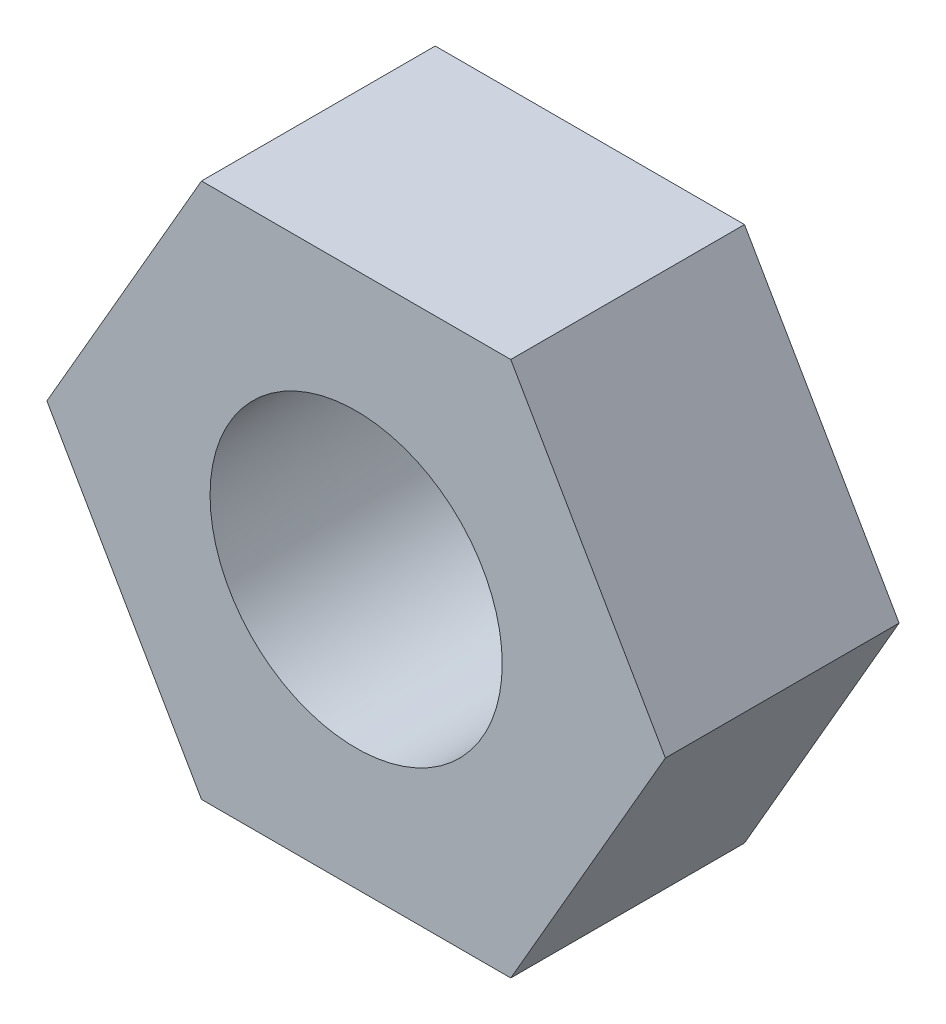
SolidWorks part; units mm, degrees
material "AISI 4340 Steel, normalized"
ref_plane "Front Plane" through (0, 0, 0) normal (0, 0, 1) x (1, 0, 0)
ref_plane "Top Plane" through (0, 0, 0) normal (0, 1, 0) x (1, 0, 0)
ref_plane "Right Plane" through (0, 0, 0) normal (1, 0, 0) x (0, 0, -1)
sketch "Sketch1" plane through (0, 0, 0) normal (0, 0, 1) x (1, 0, 0)
  line L0 (3.1754, 0) -> (1.5877, 2.75)
  line L1 (1.5877, 2.75) -> (-1.5877, 2.75)
  line L2 (-1.5877, 2.75) -> (-3.1754, 0)
  line L3 (-3.1754, 0) -> (-1.5877, -2.75)
  line L4 (-1.5877, -2.75) -> (1.5877, -2.75)
  line L5 (1.5877, -2.75) -> (3.1754, 0)
  circle A0 centre (0, 0) radius 1.5
extrude "Nut_Thread_Major_Envelope" add sketch "Sketch1" along normal blind 2.4
